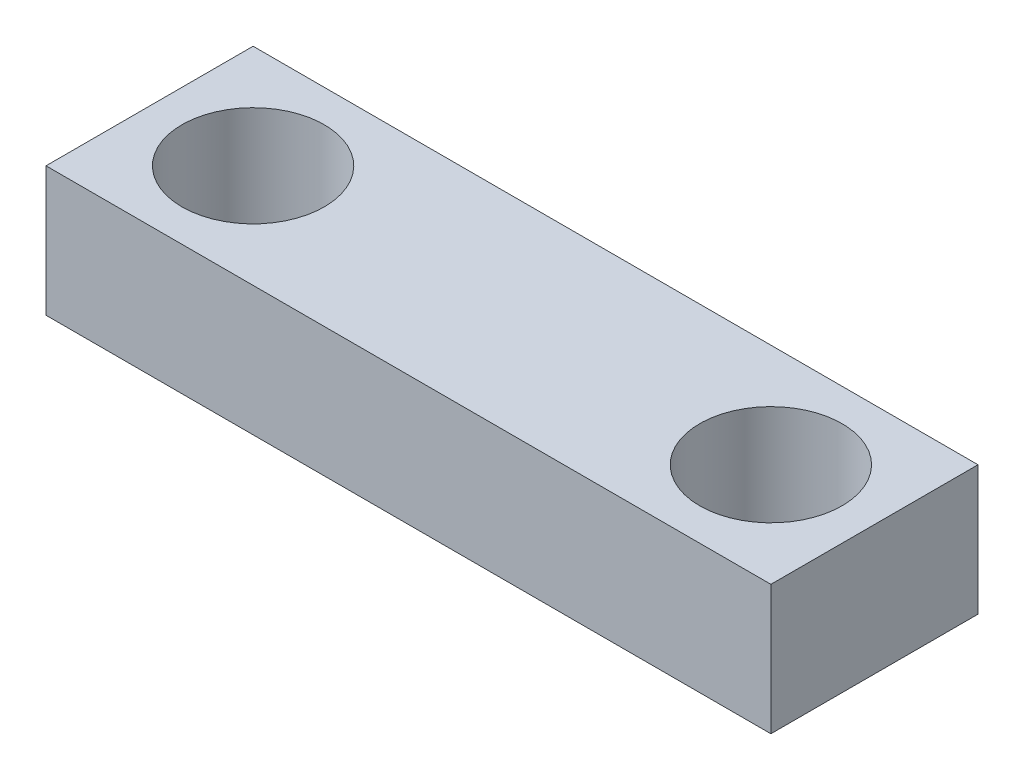
SolidWorks part; units mm, degrees
material "6061-T6 (SS)"
ref_plane "Frontal Plane" through (0, 0, 0) normal (0, 0, 1) x (1, 0, 0)
ref_plane "Horizontal Plane" through (0, 0, 0) normal (0, 1, 0) x (1, 0, 0)
ref_plane "Profile Plane" through (0, 0, 0) normal (1, 0, 0) x (0, 0, -1)
sketch "Sketch2" plane through (0, 0, 0) normal (0, 1, 0) x (1, 0, 0)
  line L1 (-14, -4) -> (14, -4)
  line L2 (-14, -4) -> (-14, 4)
  line L3 (-14, 4) -> (14, 4)
  line L4 (14, -4) -> (14, 4)
  line L5 (-14, -4) -> (14, 4) construction
  line L6 (-14, 4) -> (14, -4) construction
  circle A0 centre (10, 0) radius 2.75
  circle A1 centre (-10, 0) radius 2.75
  point P0 (0, 0)
  dimension "D5" = 5.5
  dimension "D1" = 8
  dimension "D2" = 28
  dimension "D3" = 20
  dimension "D4" = 10
extrude "Boss-Extrude1" add sketch "Sketch2" along normal blind 5
